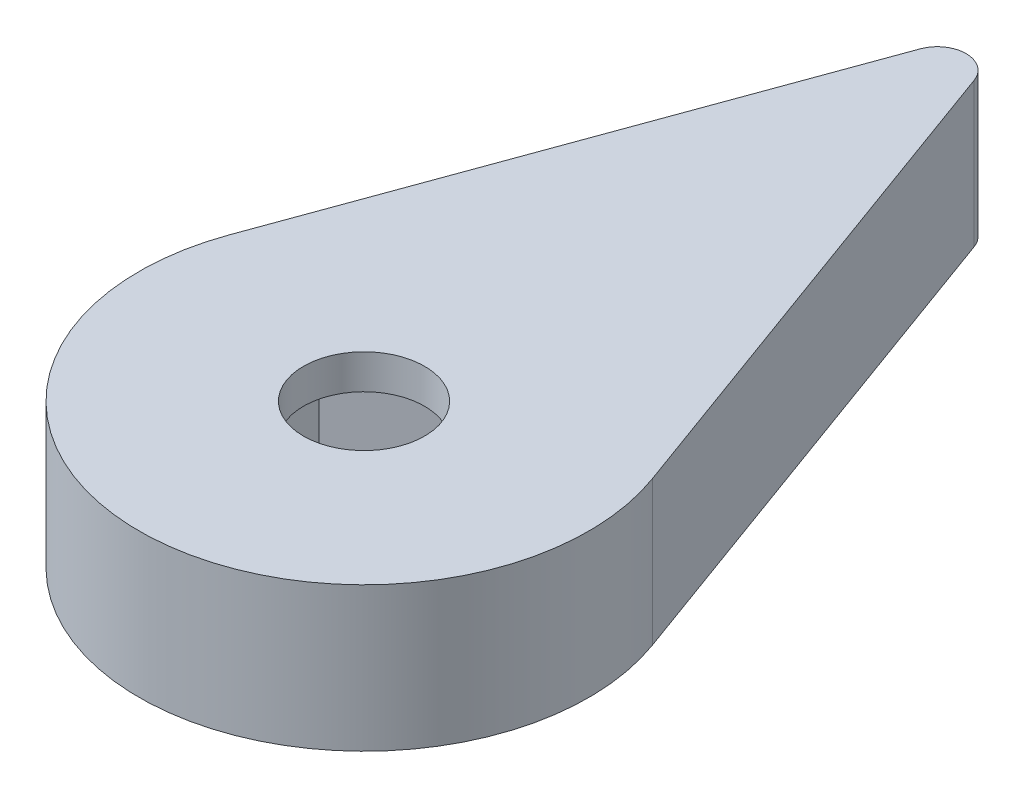
SolidWorks part; units mm, degrees
ref_plane "Front Plane" through (0, 0, 0) normal (0, 0, 1) x (1, 0, 0)
ref_plane "Top Plane" through (0, 0, 0) normal (0, 1, 0) x (1, 0, 0)
ref_plane "Right Plane" through (0, 0, 0) normal (1, 0, 0) x (0, 0, -1)
sketch "Sketch1" plane through (0, 0, 0) normal (0, 1, 0) x (1, 0, 0)
  line L3 (0, -55) -> (0, 55) construction
  line L12 (-0.9397, 20.2239) -> (-7.3296, 2.6678)
  line L15 (7.3296, 2.6678) -> (0.9397, 20.2239)
  arc A0 (-7.3296, 2.6678) -> (7.3296, 2.6678) centre (0, 0) ccw
  arc A12 (0.9397, 20.2239) -> (-0.9397, 20.2239) centre (0, 19.8819) ccw
  dimension "D1" = 7.8
  dimension "D3" = 1
  dimension "D5" = 40
extrude "Boss-Extrude2" add sketch "Sketch1" along normal blind 5
sketch "Sketch3" plane through (0, 5, 0) normal (0, 1, 0) x (1, 0, 0)
  circle A0 centre (0, 0) radius 2.1
  dimension "D1" = 4.2
extrude "Cut-Extrude1" cut sketch "Sketch3" against normal up to next
sketch "Sketch4" plane through (0, 5, 0) normal (0, 1, 0) x (1, 0, 0)
  line L1 (0, 4.2724) -> (-3.7, 2.1362)
  line L2 (-3.7, 2.1362) -> (-3.7, -2.1362)
  line L3 (-3.7, -2.1362) -> (0, -4.2724)
  line L4 (0, -4.2724) -> (3.7, -2.1362)
  line L5 (3.7, -2.1362) -> (3.7, 2.1362)
  line L6 (3.7, 2.1362) -> (0, 4.2724)
  circle A1 centre (0, 0) radius 3.7 construction
  dimension "D1" = 7.4
extrude "Cut-Extrude2" cut sketch "Sketch4" against normal blind 3.6 from offset 1.2
